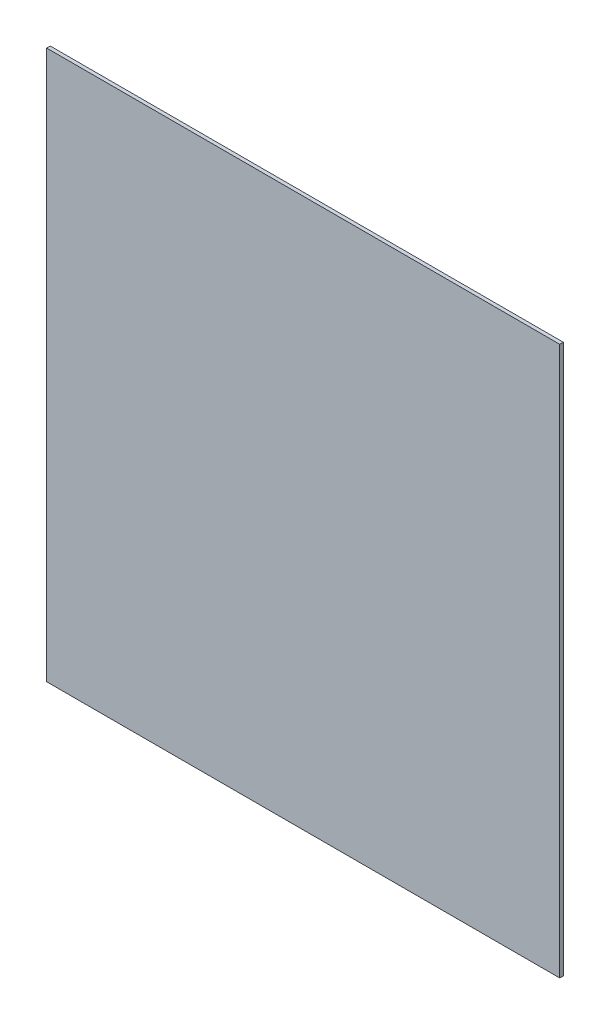
SolidWorks part; units mm, degrees
ref_plane "Front Plane" through (0, 0, 0) normal (0, 0, 1) x (1, 0, 0)
ref_plane "Top Plane" through (0, 0, 0) normal (0, 1, 0) x (1, 0, 0)
ref_plane "Right Plane" through (0, 0, 0) normal (1, 0, 0) x (0, 0, -1)
sketch "Sketch1" plane through (0, 0, 0) normal (0, 0, 1) x (1, 0, 0)
  line L0 (0, 427.6735) -> (0, 0) construction
  line L1 (0, 0) -> (427.6735, 0) construction
  line L3 (-215, 230) -> (215, 230)
  line L4 (-215, 230) -> (-215, -230)
  line L5 (-215, -230) -> (215, -230)
  line L6 (215, 230) -> (215, -230)
  dimension "D1" = 460
  dimension "D2" = 430
extrude "Boss-Extrude1" add sketch "Sketch1" along normal blind 3
